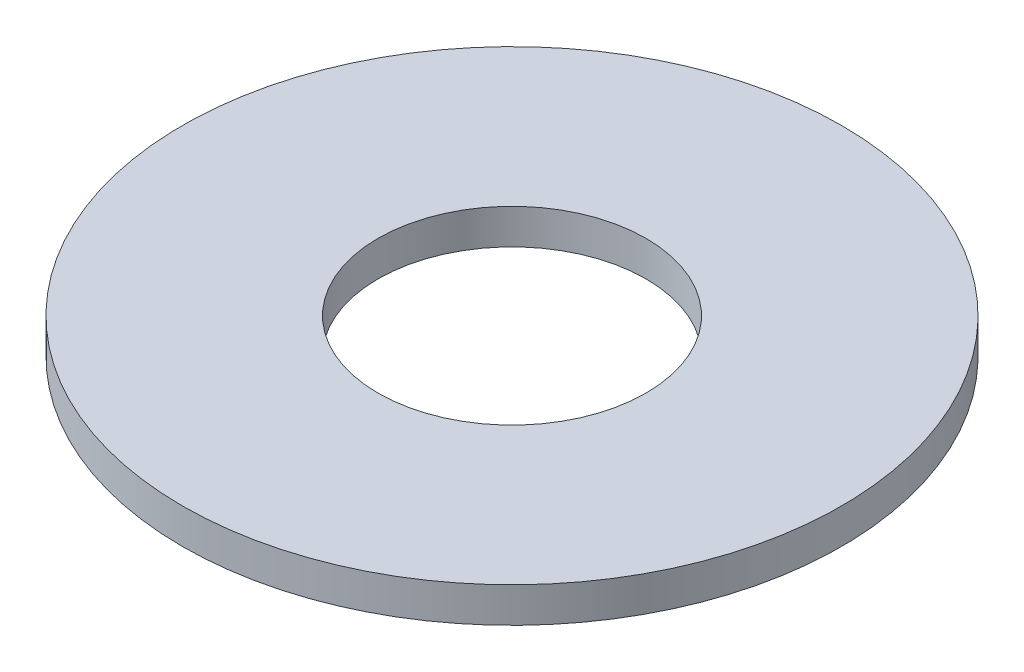
SolidWorks part; units mm, degrees
ref_plane "Front Plane" through (0, 0, 0) normal (0, 0, 1) x (1, 0, 0)
ref_plane "Top Plane" through (0, 0, 0) normal (0, 1, 0) x (1, 0, 0)
ref_plane "Right Plane" through (0, 0, 0) normal (1, 0, 0) x (0, 0, -1)
sketch "Sketch2" plane through (0, 0, 0) normal (0, 1, 0) x (1, 0, 0)
  circle A0 centre (0, 0) radius 7.625
  circle A1 centre (0, 0) radius 18.75
  dimension "D1" = 15.25
  dimension "D2" = 37.5
extrude "Boss-Extrude1" add sketch "Sketch2" along normal blind 2
